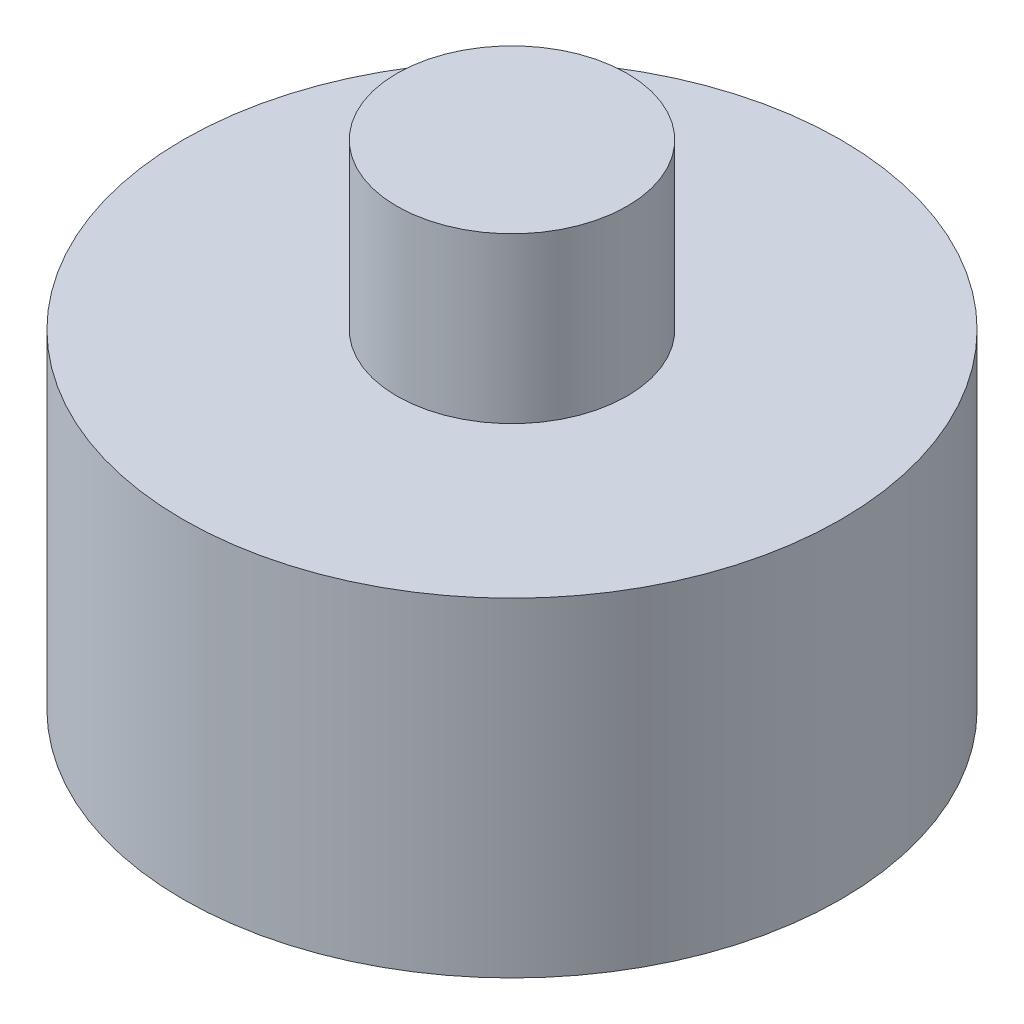
SolidWorks part; units mm, degrees
ref_plane "Front Plane" through (0, 0, 0) normal (0, 0, 1) x (1, 0, 0)
ref_plane "Top Plane" through (0, 0, 0) normal (0, 1, 0) x (1, 0, 0)
ref_plane "Right Plane" through (0, 0, 0) normal (1, 0, 0) x (0, 0, -1)
sketch "Sketch2" plane through (0, 0, 0) normal (0, 1, 0) x (1, 0, 0)
  circle A0 centre (0, 0) radius 10
  dimension "D1" = 20
extrude "Boss-Extrude1" add sketch "Sketch2" along normal blind 10
sketch "Sketch3" plane through (0, 10, 0) normal (0, 1, 0) x (1, 0, 0)
  circle A0 centre (0, 0) radius 3.5
  dimension "D1" = 7
extrude "Boss-Extrude3" add sketch "Sketch3" along normal blind 5
sketch "Sketch4" plane through (0, 0, 0) normal (0, -1, 0) x (1, 0, 0)
  circle A0 centre (0, 0) radius 8
  circle A1 centre (0, 0.1085) radius 3.75
  dimension "D1" = 7.5
  dimension "D2" = 16
